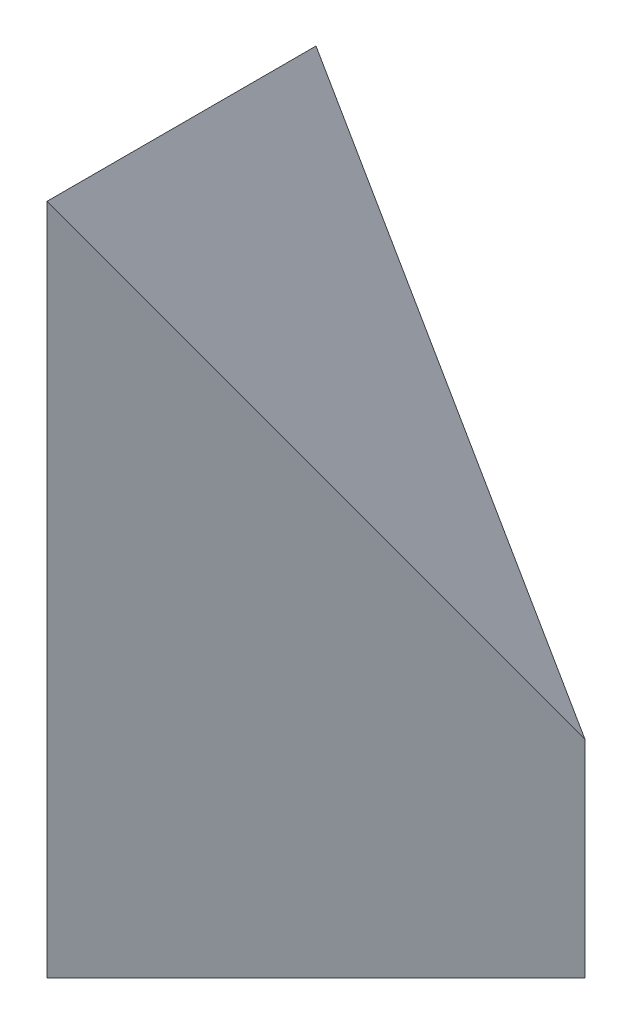
SolidWorks part; units mm, degrees
ref_plane "Front Plane" through (0, 0, 0) normal (0, 0, 1) x (1, 0, 0)
ref_plane "Top Plane" through (0, 0, 0) normal (0, 1, 0) x (1, 0, 0)
ref_plane "Right Plane" through (0, 0, 0) normal (1, 0, 0) x (0, 0, -1)
sketch "Sketch1" plane through (0, 0, 0) normal (0, 1, 0) x (1, 0, 0)
  line L0 (0, 31.75) -> (0, -19.05)
  line L1 (0, -19.05) -> (50.8, 31.75)
  line L2 (0, 31.75) -> (50.8, 31.75)
  dimension "D1" = 50.8
extrude "Boss-Extrude1" add sketch "Sketch1" along normal blind 127
sketch "Sketch3" plane through (0, 0, 0) normal (0, 0, 1) x (1, 0, 0)
  line L0 (0, 127) -> (50.8, 39.0118)
  line L1 (50.8, 127) -> (50.8, 0) construction
  line L2 (0, 127) -> (0, 0) construction
  dimension "D1" = 30
extrude "Cut-Extrude1" cut sketch "Sketch3" against normal through all and the other way through all
